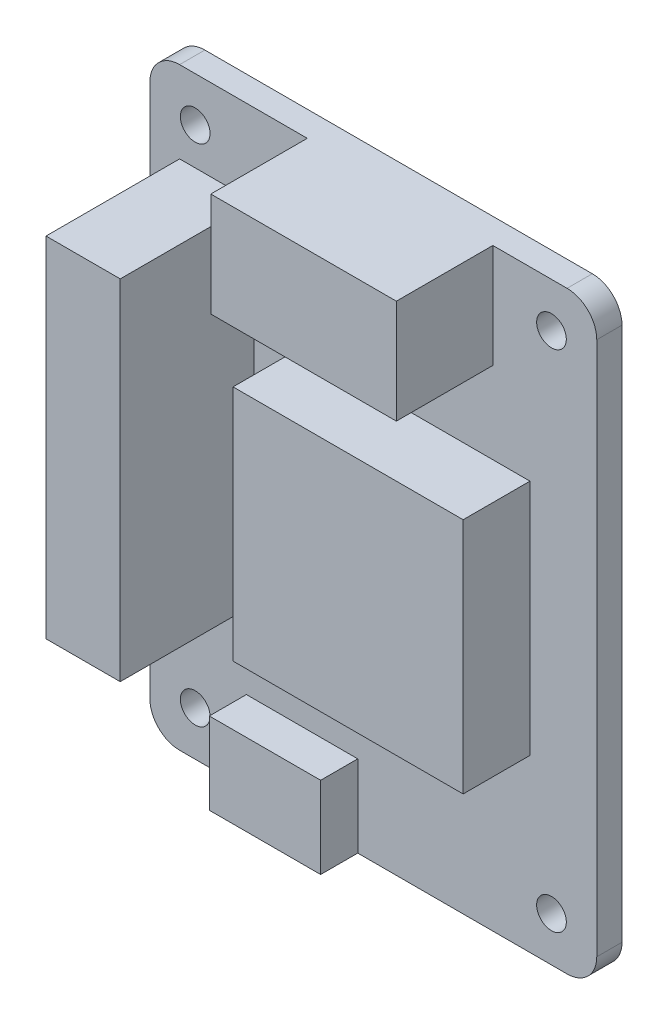
SolidWorks part; units mm, degrees
ref_plane "Front" through (0, 0, 0) normal (0, 0, 1) x (1, 0, 0)
ref_plane "Top" through (0, 0, 0) normal (0, 1, 0) x (1, 0, 0)
ref_plane "Right" through (0, 0, 0) normal (1, 0, 0) x (0, 0, -1)
sketch "草图1" plane through (0, 0, 0) normal (0, 0, 1) x (1, 0, 0)
  line L1 (15.05, -20) -> (-15.05, -20)
  line L2 (15.05, -20) -> (15.05, 20)
  line L3 (15.05, 20) -> (-15.05, 20)
  line L4 (-15.05, -20) -> (-15.05, 20)
  line L5 (15.05, -20) -> (-15.05, 20) construction
  line L6 (15.05, 20) -> (-15.05, -20) construction
  line L7 (12, -17) -> (-12, -17) construction
  line L8 (12, -17) -> (12, 17) construction
  line L9 (12, 17) -> (-12, 17) construction
  line L10 (-12, -17) -> (-12, 17) construction
  line L11 (12, -17) -> (-12, 17) construction
  line L12 (12, 17) -> (-12, -17) construction
  circle A0 centre (12, 17) radius 1
  circle A1 centre (-12, 17) radius 1
  circle A2 centre (-12, -17) radius 1
  circle A3 centre (12, -17) radius 1
  point P0 (0, 0)
  point P6 (0, 0)
  dimension "D5" = 2
  dimension "D1" = 30.1
  dimension "D2" = 40
  dimension "D3" = 34
  dimension "D4" = 24
extrude "凸台-拉伸1" add sketch "草图1" along normal blind 1.7
sketch "草图2" plane through (0, 0, 1.7) normal (0, 0, 1) x (1, 0, 0)
  line L0 (-15.05, 20) -> (-15.05, -20) construction
  line L1 (-8.05, -9) -> (-13.05, -9)
  line L2 (-8.05, -9) -> (-8.05, 14.5)
  line L3 (-8.05, 14.5) -> (-13.05, 14.5)
  line L4 (-13.05, -9) -> (-13.05, 14.5)
  line L5 (-8.05, -9) -> (-13.05, 14.5) construction
  line L6 (-8.05, 14.5) -> (-13.05, -9) construction
  line L7 (15.05, 20) -> (-15.05, 20) construction
  point P0 (-10.55, 2.75)
  dimension "D1" = 5
  dimension "D2" = 23.5
  dimension "D3" = 2
  dimension "D4" = 5.5
extrude "凸台-拉伸2" add sketch "草图2" along normal blind 9
sketch "草图3" plane through (0, 0, 1.7) normal (0, 0, 1) x (1, 0, 0)
  line L0 (15.05, -20) -> (15.05, 20) construction
  line L1 (10.55, -8.5) -> (-4.95, -8.5)
  line L2 (10.55, -8.5) -> (10.55, 7.5)
  line L3 (10.55, 7.5) -> (-4.95, 7.5)
  line L4 (-4.95, -8.5) -> (-4.95, 7.5)
  line L5 (10.55, -8.5) -> (-4.95, 7.5) construction
  line L6 (10.55, 7.5) -> (-4.95, -8.5) construction
  line L7 (15.05, 20) -> (-15.05, 20) construction
  point P0 (2.8, -0.5)
  dimension "D1" = 4.5
  dimension "D2" = 15.5
  dimension "D3" = 16
  dimension "D4" = 12.5
extrude "凸台-拉伸3" add sketch "草图3" along normal blind 4.5
sketch "草图4" plane through (0, 0, 1.7) normal (0, 0, 1) x (1, 0, 0)
  line L0 (-4.45, 20) -> (-4.45, 13)
  line L1 (15.05, 20) -> (-15.05, 20) construction
  line L2 (-4.45, 13) -> (8.05, 13)
  line L3 (8.05, 13) -> (8.05, 20)
  line L4 (8.05, 20) -> (-4.45, 20)
  line L5 (15.05, -20) -> (15.05, 20) construction
  dimension "D1" = 12.5
  dimension "D2" = 7
  dimension "D3" = 7
extrude "凸台-拉伸4" add sketch "草图4" along normal blind 6.5
sketch "草图5" plane through (0, 0, 1.7) normal (0, 0, 1) x (1, 0, 0)
  line L0 (-8.55, -20) -> (-8.55, -14.5)
  line L1 (-15.05, -20) -> (15.05, -20) construction
  line L2 (-8.55, -14.5) -> (-1.05, -14.5)
  line L3 (-1.05, -14.5) -> (-1.05, -20)
  line L4 (-1.05, -20) -> (-8.55, -20)
  line L5 (-15.05, 20) -> (-15.05, -20) construction
  dimension "D1" = 5.5
  dimension "D2" = 7.5
  dimension "D3" = 6.5
extrude "凸台-拉伸5" add sketch "草图5" along normal blind 2.5
fillet "圆角1" radius 2 4 edges at (-15.05, -20, 0.85) (15.05, -20, 0.85) (-15.05, 20, 0.85) (15.05, 20, 0.85)
